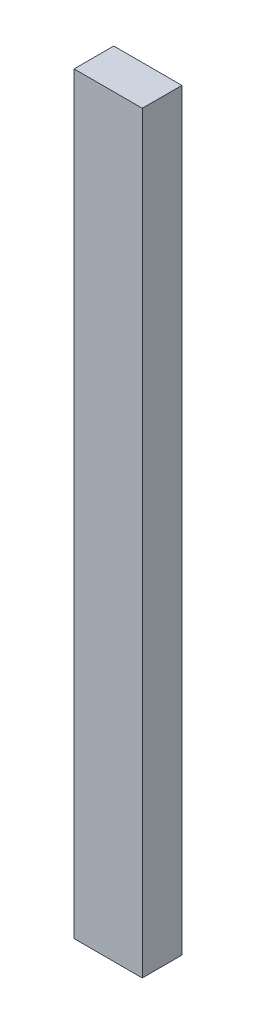
SolidWorks part; units mm, degrees
ref_plane "Front Plane" through (0, 0, 0) normal (0, 0, 1) x (1, 0, 0)
ref_plane "Top Plane" through (0, 0, 0) normal (0, 1, 0) x (1, 0, 0)
ref_plane "Right Plane" through (0, 0, 0) normal (1, 0, 0) x (0, 0, -1)
sketch "Sketch1" plane through (0, 0, 0) normal (0, 1, 0) x (1, 0, 0)
  line L1 (0, 0) -> (25.4, 0)
  line L2 (0, 0) -> (0, 25.4)
  line L3 (0, 25.4) -> (25.4, 25.4)
  line L4 (25.4, 0) -> (25.4, 25.4)
  dimension "D1" = 25.4
  dimension "D2" = 25.4
extrude "Boss-Extrude1" add sketch "Sketch1" along normal blind 482.6
sketch "Sketch2" plane through (0, 0, -25.4) normal (0, 0, -1) x (-1, 0, 0)
  line L0 (-25.4, 482.6) -> (0, 482.6) construction
  line L1 (-25.4, 482.6) -> (-25.4, 0) construction
  circle A0 centre (-12.7, 469.9) radius 6.35
  point P2 (-123.9699, 438.5964)
  point P3 (0, 0)
  point P6 (-12.7, 482.6)
  point P11 (-21.1614, 482.6)
  dimension "D1" = 12.7
  dimension "D2" = 12.7
extrude "Boss-Extrude2" add sketch "Sketch2" along normal blind 6.35
sketch "Sketch3" plane through (0, 0, 0) normal (-1, 0, 0) x (0, 0, 1)
  line L1 (0, 0) -> (-25.4, 0)
  line L2 (0, 0) -> (0, 482.6)
  line L3 (0, 482.6) -> (-25.4, 482.6)
  line L4 (-25.4, 0) -> (-25.4, 482.6)
extrude "Boss-Extrude3" add sketch "Sketch3" along normal blind 18.288
